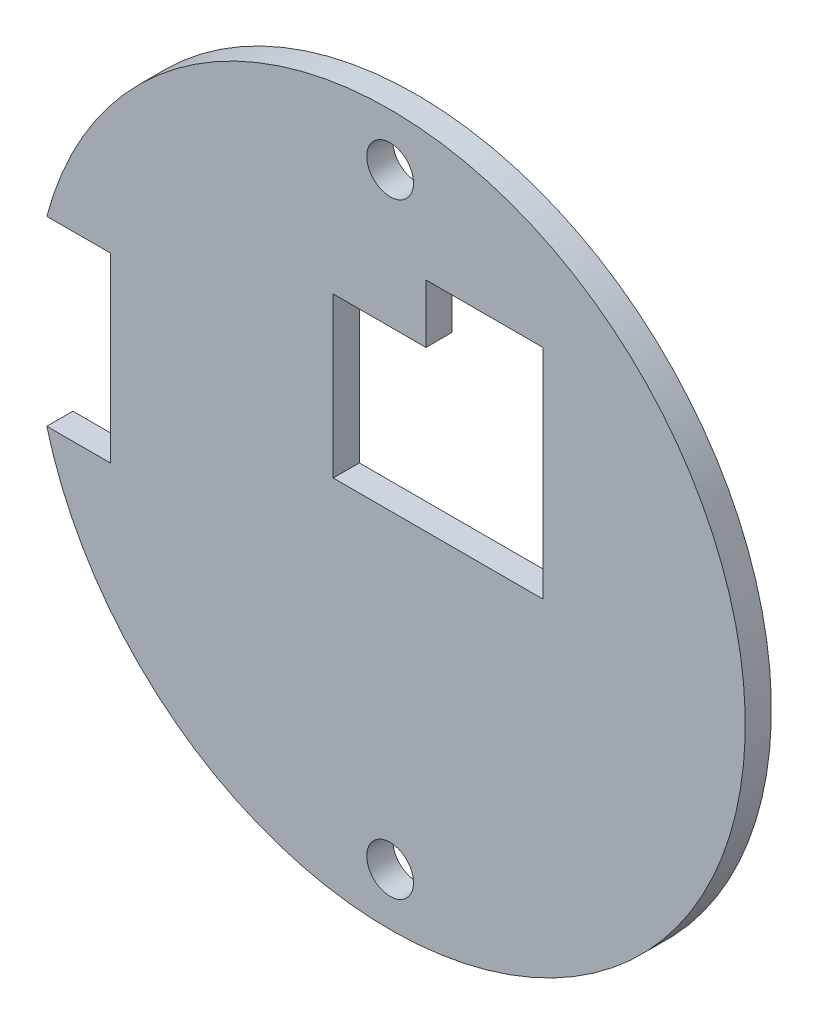
SolidWorks part; units mm, degrees
ref_plane "Front Plane" through (0, 0, 0) normal (0, 0, 1) x (1, 0, 0)
ref_plane "Top Plane" through (0, 0, 0) normal (0, 1, 0) x (1, 0, 0)
ref_plane "Right Plane" through (0, 0, 0) normal (1, 0, 0) x (0, 0, -1)
sketch "Sketch1" plane through (0, 0, 0) normal (0, 0, 1) x (1, 0, 0)
  line L0 (9.2901, 13.7033) -> (2.1781, 13.7033)
  line L1 (2.1781, 13.7033) -> (2.1781, 10.1473)
  line L2 (2.1781, 10.1473) -> (-3.4607, 10.1473)
  line L3 (-3.4607, 10.1473) -> (-3.4607, 0.4572)
  line L4 (-3.4607, 0.4572) -> (9.2901, 0.4572)
  line L5 (9.2901, 0.4572) -> (9.2901, 13.7033)
  line L7 (2.9147, 0.4572) -> (2.9147, -0.8128) construction
  line L8 (-16.9841, 5.5245) -> (-20.8712, 5.5245)
  line L9 (-16.9841, 0) -> (0, 0) construction
  line L10 (-16.9841, -5.5245) -> (-20.8712, -5.5245)
  line L11 (0, 18.415) -> (0, -18.415) construction
  line L16 (-16.9841, 5.5245) -> (-16.9841, -5.5245)
  arc A3 (-20.8712, -5.5245) -> (-20.8712, 5.5245) centre (0, 0) ccw
  circle A4 centre (0, 18.415) radius 1.4224
  circle A5 centre (0, -18.415) radius 1.4224
  dimension "D7" = 3.8872
  dimension "D8" = 2.8448
  dimension "D1" = 0.4572
  dimension "D2" = 13.2461
  dimension "D3" = 12.7508
  dimension "D4" = 3.556
  dimension "D5" = 7.112
  dimension "D6" = 11.049
  dimension "D9" = 16.9841
  dimension "D10" = 3.4607
extrude "Boss-Extrude1" add sketch "Sketch1" along normal blind 1.5875
